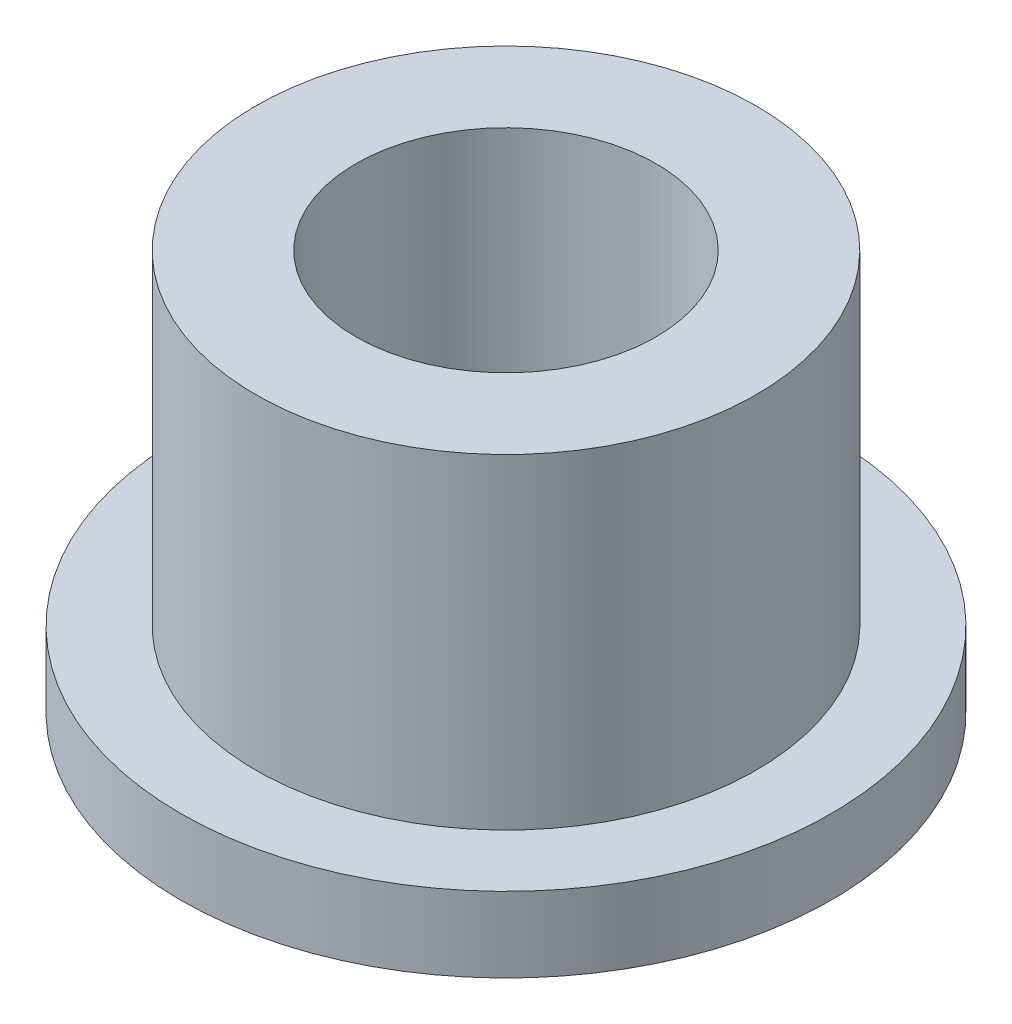
SolidWorks part; units mm, degrees
ref_plane "前基準面" through (0, 0, 0) normal (0, 0, 1) x (1, 0, 0)
ref_plane "上基準面" through (0, 0, 0) normal (0, 1, 0) x (1, 0, 0)
ref_plane "右基準面" through (0, 0, 0) normal (1, 0, 0) x (0, 0, -1)
sketch "草圖1" plane through (0, 0, 0) normal (0, 1, 0) x (1, 0, 0)
  circle A0 centre (0, 0) radius 13
  circle A1 centre (0, 0) radius 6
  dimension "D1" = 26
  dimension "D2" = 12
extrude "填料-伸長1" add sketch "草圖1" along normal blind 3
sketch "草圖2" plane through (0, 3, 0) normal (0, 1, 0) x (1, 0, 0)
  circle A0 centre (0, 0) radius 10
  circle A1 centre (0, 0) radius 6
  dimension "D1" = 20
  dimension "D2" = 12
extrude "填料-伸長2" add sketch "草圖2" along normal blind 13
